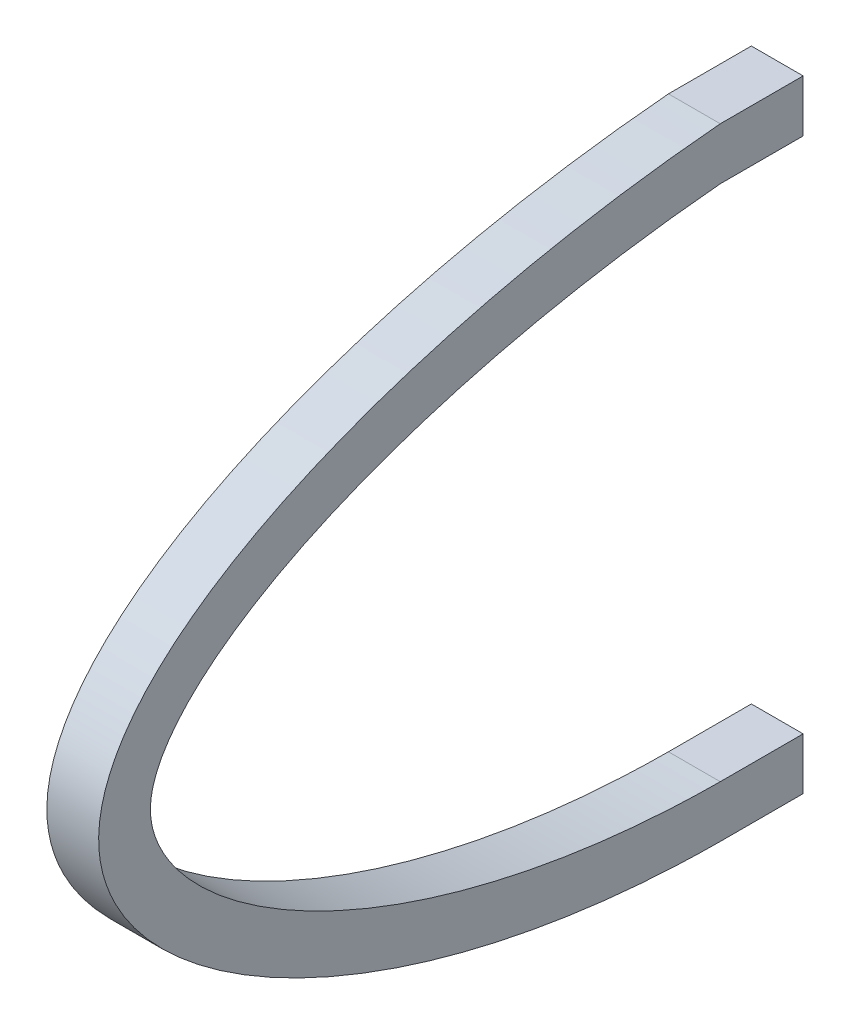
SolidWorks part; units mm, degrees
ref_plane "Front Plane" through (0, 0, 0) normal (0, 0, 1) x (1, 0, 0)
ref_plane "Top Plane" through (0, 0, 0) normal (0, 1, 0) x (1, 0, 0)
ref_plane "Right Plane" through (0, 0, 0) normal (1, 0, 0) x (0, 0, -1)
sketch "Sketch1" plane through (0, 0, 0) normal (1, 0, 0) x (0, 0, -1)
  line L0 (0, 30.0098) -> (8, 30.0098)
  line L2 (0, 30.0098) -> (0, 24.9901)
  line L3 (0, -24.9901) -> (0, -29.9902)
  line L4 (0, 24.9901) -> (0, -24.9901) construction
  line L5 (8, 30.0098) -> (8, 24.9901)
  line L6 (8, 24.9901) -> (0, 24.9901)
  line L7 (0, -24.9901) -> (8, -24.9901)
  line L8 (8, -24.9901) -> (8, -29.9902)
  line L9 (8, -29.9902) -> (0, -29.9902)
  spline S2 degree 3 poles (0, 30.0098) (-33.8658, 27.0412) (-86.5989, 1.388) (-32.9365, -29.8091) (0, -29.9902) knots 0 0 0 0 0.500032 1 1 1 1
  spline S3 degree 1 poles (0.4366, 25.0289) (0.0275, -24.9902) knots 0 0 1 1 construction
  spline S4 degree 3 poles (0.4366, 25.0289) (-0.583, 24.9396) (-2.6305, 24.7402) (-6.6375, 24.2711) (-11.5254, 23.5525) (-17.1505, 22.4931) (-24.2953, 20.8362) (-32.4795, 18.3431) (-40.8506, 14.8062) (-47.5011, 10.8932) (-52.1591, 6.846) (-54.2152, 3.7253) (-54.911, 1.5726) (-55.0581, 0.097) (-54.8608, -1.4562) (-54.0406, -3.836) (-51.7657, -7.2999) (-46.9245, -11.7099) (-40.2077, -15.9144) (-31.8912, -19.6037) (-23.8584, -22.0398) (-16.9038, -23.4968) (-11.457, -24.3181) (-6.7494, -24.7557) (-2.9051, -24.9454) (-0.9473, -24.9849) (0.0275, -24.9902) knots 0 0 0 0 0.015625 0.03125 0.0625 0.09375 0.125 0.1875 0.25 0.3125 0.375 0.4375 0.46875 0.5 0.53125 0.5625 0.625 0.6875 0.75 0.8125 0.875 0.90625 0.9375 0.96875 0.984375 1 1 1 1 only from (0, 24.9901) to (0, -24.9901)
  spline S5 degree 3 poles (0.263, 25.0133) (0.1982, 25.0076) (0.1096, 24.9998) (0.0219, 24.992) (0, 24.9901) knots 0 0 0 0 0.000983 0.001311 0.001311 0.001311 0.001311 construction
  spline S6 degree 3 poles (0, -24.9901) (0.0014, -24.9901) (0.0069, -24.9901) (0.0125, -24.9901) (0.0166, -24.9902) knots 0.999914 0.999914 0.999914 0.999914 0.999936 1 1 1 1 construction
  point P20 (0, 0)
  dimension "D5" = 60
  dimension "D6" = 60
  dimension "D1" = 8
  dimension "D8" = 5
extrude "Boss-Extrude1" add sketch "Sketch1" along normal mid plane 5 contours L2 S2 | L9 L8 L7 L3 | L6 L5 L0 L2
equation "\"D5@Sketch1\"=\"D6@Sketch1\""
